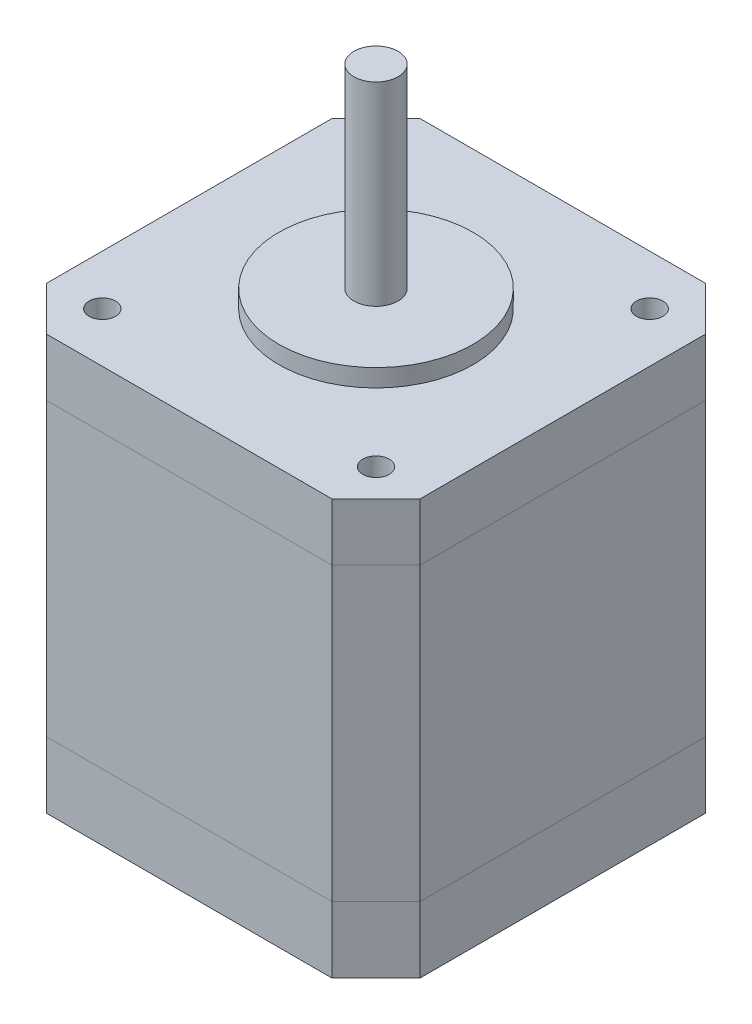
SolidWorks part; units mm, degrees
ref_plane "Front Plane" through (0, 0, 0) normal (0, 0, 1) x (1, 0, 0)
ref_plane "Top Plane" through (0, 0, 0) normal (0, 1, 0) x (1, 0, 0)
ref_plane "Right Plane" through (0, 0, 0) normal (1, 0, 0) x (0, 0, -1)
sketch "Sketch1" plane through (0, 0, 0) normal (0, 1, 0) x (1, 0, 0)
  line L0 (16.15, 21.15) -> (21.15, 16.15)
  line L1 (-16.15, 21.15) -> (16.15, 21.15)
  line L2 (-21.15, 16.15) -> (-21.15, -16.15)
  line L3 (-16.15, -21.15) -> (16.15, -21.15)
  line L4 (21.15, 16.15) -> (21.15, -16.15)
  line L5 (-21.15, 21.15) -> (21.15, -21.15) construction
  line L6 (-21.15, -21.15) -> (21.15, 21.15) construction
  line L7 (-21.15, 16.15) -> (-16.15, 21.15)
  line L8 (-21.15, -16.15) -> (-16.15, -21.15)
  line L9 (16.15, -21.15) -> (21.15, -16.15)
  point P0 (0, 0)
extrude "Extrude1" add sketch "Sketch1" along normal blind 47
sketch "Sketch2" plane through (0, 47, 0) normal (0, 1, 0) x (1, 0, 0)
  circle A0 centre (0, 0) radius 11
extrude "Extrude2" add sketch "Sketch2" along normal blind 2
sketch "Sketch3" plane through (0, 0, 0) normal (0, 1, 0) x (1, 0, 0)
  circle A0 centre (0, 0) radius 2.5
extrude "Extrude3" add sketch "Sketch3" along normal blind 80.5 from offset 9.5 offset against normal yes
sketch "Sketch4" plane through (0, 47, 0) normal (0, 1, 0) x (1, 0, 0)
  line L1 (-15.5, 15.5) -> (15.5, 15.5) construction
  line L2 (-15.5, 15.5) -> (-15.5, -15.5) construction
  line L3 (-15.5, -15.5) -> (15.5, -15.5) construction
  line L4 (15.5, 15.5) -> (15.5, -15.5) construction
  line L5 (-15.5, 15.5) -> (15.5, -15.5) construction
  line L6 (-15.5, -15.5) -> (15.5, 15.5) construction
  circle A0 centre (-15.5, 15.5) radius 1.5
  circle A1 centre (15.5, 15.5) radius 1.5
  circle A2 centre (-15.5, -15.5) radius 1.5
  circle A3 centre (15.5, -15.5) radius 1.5
  point P0 (0, 0)
extrude "Extrude4" cut sketch "Sketch4" against normal blind 4.5
ref_plane "Плоскость1" through (0, 7.5, 0) normal (0, -1, 0) x (1, 0, 0)
sketch "Эскиз2" plane through (0, 7.5, 0) normal (0, -1, 0) x (1, 0, 0)
  line L0 (-21.15, 16.15) -> (-16.15, 21.15)
  line L1 (-16.15, 21.15) -> (16.15, 21.15)
  line L2 (16.15, 21.15) -> (21.15, 16.15)
  line L3 (21.15, 16.15) -> (21.15, -16.15)
  line L4 (21.15, -16.15) -> (16.15, -21.15)
  line L5 (16.15, -21.15) -> (-16.15, -21.15)
  line L6 (-16.15, -21.15) -> (-21.15, -16.15)
  line L7 (-21.15, -16.15) -> (-21.15, 16.15)
extrude "Вытянуть3" cut sketch "Эскиз2" against normal blind 33
sketch "Эскиз3" plane through (0, 7.5, 0) normal (0, -1, 0) x (1, 0, 0)
  line L0 (-21.15, 16.15) -> (-16.15, 21.15)
  line L1 (-16.15, 21.15) -> (16.15, 21.15)
  line L2 (16.15, 21.15) -> (21.15, 16.15)
  line L3 (16.15, 21.15) -> (21.15, 16.15) construction
  line L4 (21.15, 16.15) -> (21.15, -16.15)
  line L5 (21.15, -16.15) -> (16.15, -21.15)
  line L6 (16.15, -21.15) -> (-16.15, -21.15)
  line L7 (-16.15, -21.15) -> (-21.15, -16.15)
  line L8 (-21.15, -16.15) -> (-21.15, 16.15)
extrude "Вытянуть4" add sketch "Эскиз3" against normal blind 33 separate body
